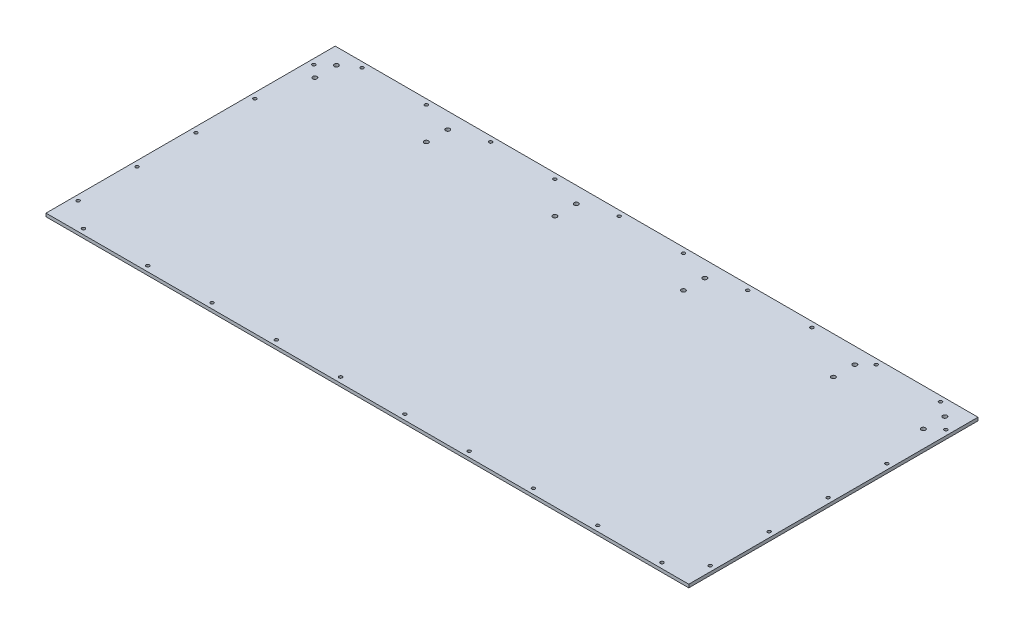
SolidWorks part; units mm, degrees
ref_plane "Front Plane" through (0, 0, 0) normal (0, 0, 1) x (1, 0, 0)
ref_plane "Top Plane" through (0, 0, 0) normal (0, 1, 0) x (1, 0, 0)
ref_plane "Right Plane" through (0, 0, 0) normal (1, 0, 0) x (0, 0, -1)
sketch "Sketch1" plane through (0, 0, 0) normal (0, 1, 0) x (1, 0, 0)
  line L1 (0, -60) -> (600, -60)
  line L2 (0, -60) -> (0, 210)
  line L3 (0, 210) -> (600, 210)
  line L4 (600, -60) -> (600, 210)
  dimension "D1" = 270
  dimension "D2" = 600
  dimension "D3" = 60
extrude "Extrude1" add sketch "Sketch1" along normal blind 3
sketch "Sketch17" plane through (0, 3, 0) normal (0, 1, 0) x (-1, 0, 0)
  line L1 (0, 1.65) -> (0, -1.65) construction
  line L2 (-600, -210) -> (0, -210) construction
  line L3 (-600, 60) -> (-600, -210) construction
  circle A0 centre (-16, -195) radius 2
  circle A1 centre (-16, -175) radius 2
  circle A2 centre (-584, -195) radius 2
  circle A3 centre (-584, -175) radius 2
  circle A4 centre (-120, -195) radius 2
  circle A5 centre (-120, -175) radius 2
  circle A6 centre (-240, -195) radius 2
  circle A7 centre (-240, -175) radius 2
  circle A8 centre (-360, -195) radius 2
  circle A9 centre (-360, -175) radius 2
  circle A10 centre (-500, -195) radius 2
  circle A11 centre (-500, -175) radius 2
  dimension "D1" = 4
  dimension "D2" = 16
  dimension "D3" = 15
  dimension "D4" = 20
  dimension "D5" = 16
  dimension "D6" = 120
  dimension "D7" = 240
  dimension "D8" = 360
  dimension "D9" = 500
  dimension "D10" = 100
extrude "Cut-Extrude10" cut sketch "Sketch17" against normal through all
sketch "Sketch18" plane through (0, 3, 0) normal (0, 1, 0) x (-1, 0, 0)
  line L0 (-600, -210) -> (0, -210) construction
  line L1 (0, 60) -> (-600, 60) construction
  line L2 (0, 1.65) -> (0, -1.65) construction
  circle A0 centre (-30, 55) radius 1.5
  circle A1 centre (-30, -205) radius 1.5
  dimension "D2" = 3
  dimension "D1" = 5
  dimension "D3" = 5
  dimension "D4" = 30
extrude "Cut-Extrude11" cut sketch "Sketch18" against normal through all
pattern_linear "LPattern1" count 10 spacing 60 along (1, 0, 0) of "Cut-Extrude11"
sketch "Sketch19" plane through (0, 3, 0) normal (0, 1, 0) x (-1, 0, 0)
  line L0 (0, 1.65) -> (0, -1.65) construction
  line L1 (-600, 60) -> (-600, -210) construction
  line L2 (-600, -210) -> (0, -210) construction
  line L4 (0, 60) -> (-600, 60) construction
  circle A0 centre (-5, -185) radius 1.5
  circle A1 centre (-5, -130) radius 1.5
  circle A2 centre (-5, -75) radius 1.5
  circle A3 centre (-5, -20) radius 1.5
  circle A4 centre (-595, -185) radius 1.5
  circle A5 centre (-595, -130) radius 1.5
  circle A6 centre (-595, -75) radius 1.5
  circle A7 centre (-595, -20) radius 1.5
  circle A8 centre (-5, 35) radius 1.5
  circle A9 centre (-595, 35) radius 1.5
  dimension "D8" = 3
  dimension "D1" = 5
  dimension "D2" = 5
  dimension "D3" = 55
  dimension "D4" = 55
  dimension "D5" = 55
  dimension "D6" = 25
  dimension "D7" = 55
  dimension "D9" = 25
extrude "Cut-Extrude12" cut sketch "Sketch19" against normal through all
